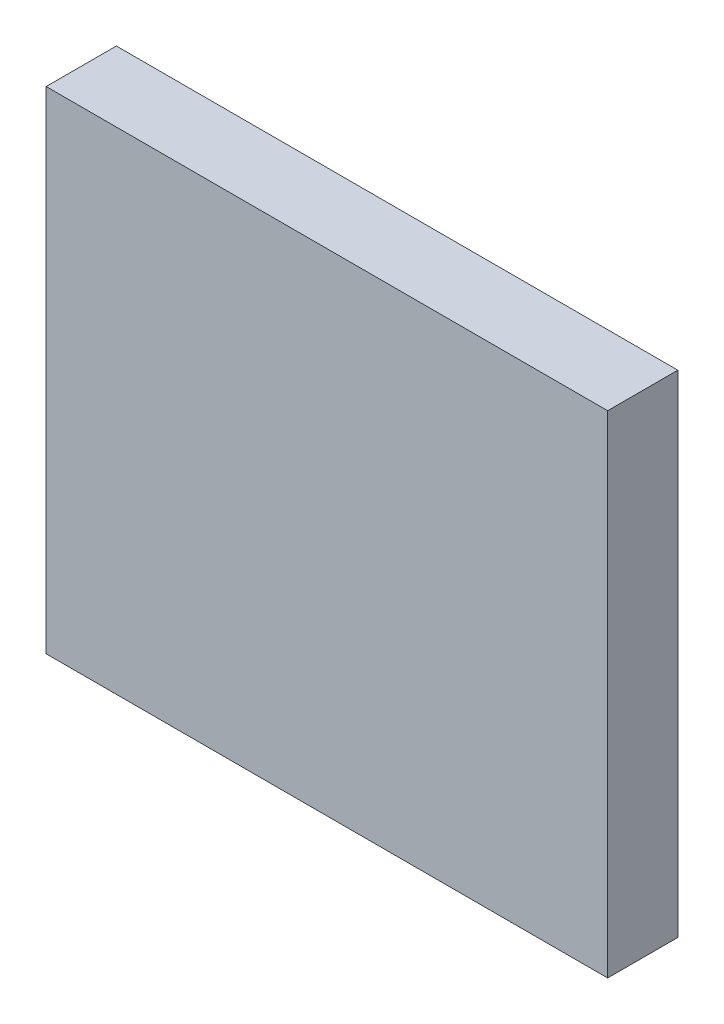
SolidWorks part; units mm, degrees
ref_plane "Plan de face" through (0, 0, 0) normal (0, 0, 1) x (1, 0, 0)
ref_plane "Plan de dessus" through (0, 0, 0) normal (0, 1, 0) x (1, 0, 0)
ref_plane "Plan de droite" through (0, 0, 0) normal (1, 0, 0) x (0, 0, -1)
sketch "Esquisse1" plane through (0, 0, 0) normal (0, 0, 1) x (1, 0, 0)
  line L1 (-40, -35) -> (40, -35)
  line L2 (-40, -35) -> (-40, 35)
  line L3 (-40, 35) -> (40, 35)
  line L4 (40, -35) -> (40, 35)
  line L5 (-40, -35) -> (40, 35) construction
  line L6 (-40, 35) -> (40, -35) construction
  point P0 (0, 0)
  dimension "D1" = 80
  dimension "D2" = 70
extrude "Boss.-Extru.1" add sketch "Esquisse1" along normal blind 10 contours L3 L4 L1 L2
